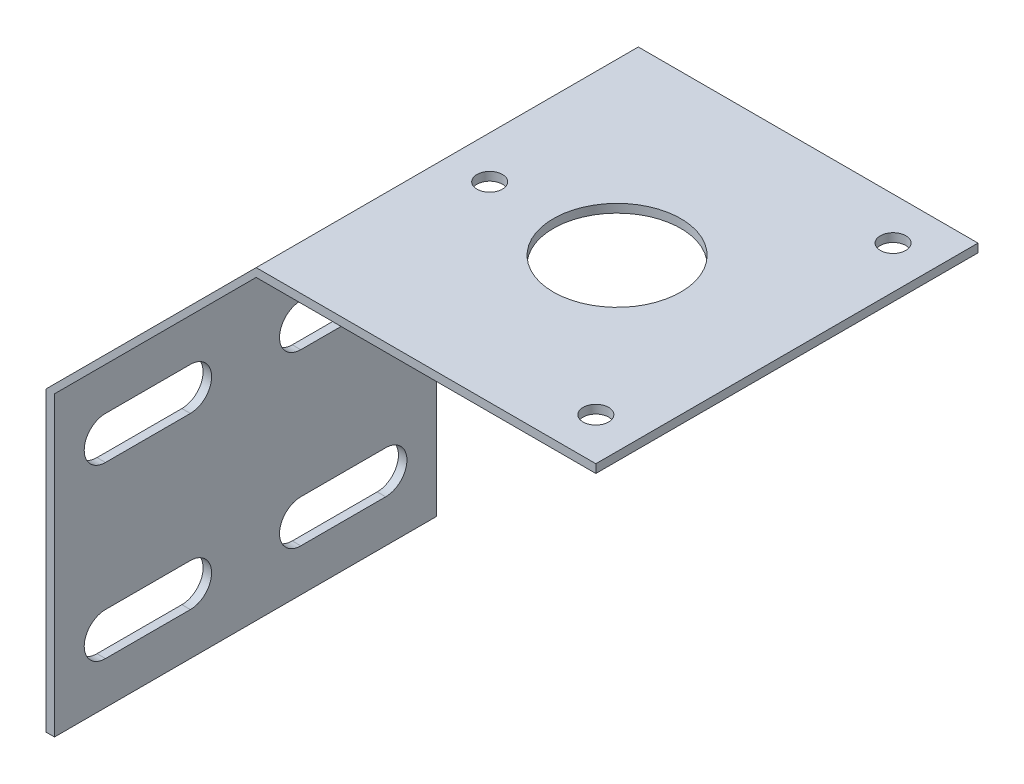
SolidWorks part; units mm, degrees
ref_plane "Front Plane" through (0, 0, 0) normal (0, 0, 1) x (1, 0, 0)
ref_plane "Top Plane" through (0, 0, 0) normal (0, 1, 0) x (1, 0, 0)
ref_plane "Right Plane" through (0, 0, 0) normal (1, 0, 0) x (0, 0, -1)
sketch "Sketch1" plane through (0, 0, 0) normal (0, 0, 1) x (1, 0, 0)
  line L0 (0, 0) -> (0, 70)
  line L1 (0, 70) -> (49.4975, 119.4975)
  line L2 (49.4975, 119.4975) -> (129.4975, 119.4975)
  line L3 (129.4975, 119.4975) -> (129.4975, 117.4975)
  line L4 (129.4975, 117.4975) -> (49.4975, 117.4975)
  line L5 (49.4975, 117.4975) -> (2, 70)
  line L6 (2, 70) -> (2, 0)
  line L7 (2, 0) -> (0, 0)
  dimension "D1" = 2
  dimension "D2" = 2
  dimension "D3" = 70
  dimension "D4" = 80
  dimension "D5" = 70
extrude "Boss-Extrude1" add sketch "Sketch1" along normal blind 90
sketch "Sketch2" plane through (0, 119.4975, 0) normal (0, 1, 0) x (1, 0, 0)
  line L0 (129.4975, 0) -> (49.4975, 0) construction
  line L1 (129.4975, -90) -> (129.4975, 0) construction
  line L2 (49.4975, -90) -> (49.4975, 0) construction
  line L3 (129.4975, -90) -> (49.4975, -90) construction
  circle A0 centre (89.4975, -45) radius 15
  circle A1 centre (59.4975, -45) radius 3
  circle A2 centre (119.4975, -10) radius 3
  circle A3 centre (119.4975, -80) radius 3
  dimension "D1" = 30
  dimension "D4" = 6
  dimension "D6" = 10
  dimension "D2" = 45
  dimension "D3" = 40
  dimension "D5" = 10
  dimension "D7" = 10
  dimension "D8" = 10
extrude "Cut-Extrude1" cut sketch "Sketch2" against normal up to surface (2 mm away) up to face at (89.4975, 117.4975, 45)
sketch "Sketch3" plane through (0, 0, 0) normal (-1, 0, 0) x (0, 0, 1)
  line L0 (12, 55) -> (32, 55) construction
  line L1 (12, 60) -> (32, 60)
  line L2 (12, 50) -> (32, 50)
  line L3 (90, 0) -> (0, 0) construction
  line L4 (90, 70) -> (90, 0) construction
  line L6 (0, 70) -> (0, 0) construction
  line L7 (90, 70) -> (0, 70) construction
  line L8 (58, 15) -> (78, 15) construction
  line L9 (58, 20) -> (78, 20)
  line L10 (58, 10) -> (78, 10)
  line L11 (58, 55) -> (78, 55) construction
  line L12 (58, 60) -> (78, 60)
  line L13 (58, 50) -> (78, 50)
  line L14 (12, 15) -> (32, 15) construction
  line L15 (12, 20) -> (32, 20)
  line L16 (12, 10) -> (32, 10)
  arc A0 (12, 60) -> (12, 50) centre (12, 55) ccw
  arc A1 (32, 50) -> (32, 60) centre (32, 55) ccw
  arc A2 (58, 20) -> (58, 10) centre (58, 15) ccw
  arc A3 (78, 10) -> (78, 20) centre (78, 15) ccw
  arc A4 (58, 60) -> (58, 50) centre (58, 55) ccw
  arc A5 (78, 50) -> (78, 60) centre (78, 55) ccw
  arc A6 (12, 20) -> (12, 10) centre (12, 15) ccw
  arc A7 (32, 10) -> (32, 20) centre (32, 15) ccw
  point P2 (22, 55)
  point P7 (7, 55)
  point P14 (68, 15)
  point P22 (68, 55)
  point P29 (22, 15)
  point P34 (0, 0)
  point P35 (0, 0)
  point P36 (0, 0)
  point P37 (0, 0)
  point P39 (83, 15)
  dimension "D1" = 7
  dimension "D2" = 10
  dimension "D3" = 20
  dimension "D4" = 10
  dimension "D5" = 10
  dimension "D6" = 7
extrude "Cut-Extrude2" cut sketch "Sketch3" against normal up to surface (2 mm away) up to face at (2, 35, 45)
